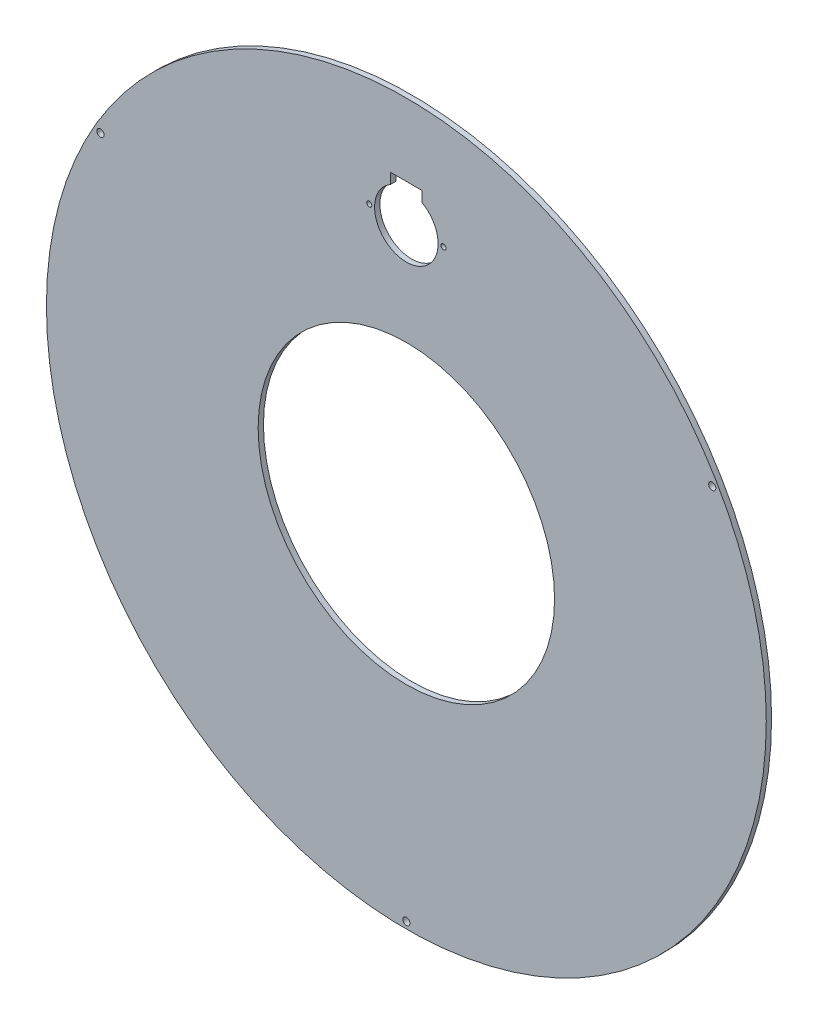
SolidWorks part; units mm, degrees
ref_plane "Piano frontale" through (0, 0, 0) normal (0, 0, 1) x (1, 0, 0)
ref_plane "Piano superiore" through (0, 0, 0) normal (0, 1, 0) x (1, 0, 0)
ref_plane "Piano destro" through (0, 0, 0) normal (1, 0, 0) x (0, 0, -1)
sketch "Schizzo1" plane through (0, 0, 0) normal (0, 0, 1) x (1, 0, 0)
  circle A0 centre (0, 0) radius 170
  circle A1 centre (0, 0) radius 70
  dimension "D1" = 340
  dimension "D2" = 140
extrude "Estrusione-Estrusione1" add sketch "Schizzo1" along normal blind 2.5
sketch "Schizzo3" plane through (0, 0, 2.5) normal (0, 0, 1) x (1, 0, 0)
  line L1 (7.5, 135.8404) -> (-7.5, 135.8404)
  line L2 (7.5, 135.8404) -> (7.5, 130.8404)
  line L4 (-7.5, 135.8404) -> (-7.5, 130.8404)
  arc A0 (-7.5, 130.8404) -> (7.5, 130.8404) centre (0, 117.85) ccw
  point P2 (0, 132.85)
  dimension "D1" = 30
  dimension "D2" = 117.85
  dimension "D3" = 15
  dimension "D4" = 5
extrude "Taglio-Estrusione1" cut sketch "Schizzo3" against normal up to surface (2.5 mm away) up to face at (170, 0, 0)
sketch "Schizzo4" plane through (0, 0, 2.5) normal (0, 0, 1) x (1, 0, 0)
  line L0 (0, 0) -> (-17.5117, 117.8483) construction
  line L1 (0, 0) -> (0, 23.2224) construction
  line L3 (0, -1.375) -> (0, 1.375) construction
  line L4 (0, 0) -> (17.5117, 117.8483) construction
  dimension "D1" = 8.452
  dimension "D2" = 119.1422
hole_wizard "Foro per Vite M2-1" positions "Schizzo5" profile "Schizzo6" hole size "M2" standard "ISO" end condition up to next
sketch "Schizzo5" plane through (0, 0, 2.5) normal (0, 0, 1) x (1, 0, 0)
  point P0 (17.5117, 117.8483)
  point P3 (-17.5117, 117.8483)
sketch "Schizzo6" plane through (17.5117, 117.8483, 2.5) normal (1, 0, 0) x (0, -1, 0)
  line L0 (0, 0) -> (0, 2.5)
  line L1 (0, 2.5) -> (1.2, 2.5)
  line L2 (1.2, 2.5) -> (1.2, 0)
  line L5 (1.2, 0) -> (0, 0)
  line L11 (0, -6.35) -> (0, 107.95) construction
  dimension "Thru Hole Dia." = 2.4
  dimension "Thru Hole Depth" = 2.5
sketch "Schizzo7" plane through (0, 0, 2.5) normal (0, 0, 1) x (1, 0, 0)
  line L0 (0, 0) -> (0, -166.8304) construction
  dimension "D1" = 166.8304
hole_wizard "Foro per Vite M3-1" positions "Schizzo8" profile "Schizzo9" hole size "M3" standard "ISO" end condition up to next
sketch "Schizzo8" plane through (0, 0, 2.5) normal (0, 0, 1) x (1, 0, 0)
  point P0 (0, -166.8304)
sketch "Schizzo9" plane through (0, -166.8304, 2.5) normal (1, 0, 0) x (0, -1, 0)
  line L0 (0, 0) -> (0, 2.5)
  line L1 (0, 2.5) -> (1.7, 2.5)
  line L2 (1.7, 2.5) -> (1.7, 0)
  line L5 (1.7, 0) -> (0, 0)
  line L11 (0, -6.35) -> (0, 107.95) construction
  dimension "Thru Hole Dia." = 3.4
  dimension "Thru Hole Depth" = 2.5
pattern_circular "RipetizioneCircolare1" count 3 over 360 about axis through (0, 0, 0) along (0, 0, 1) of "Foro per Vite M3-1"
